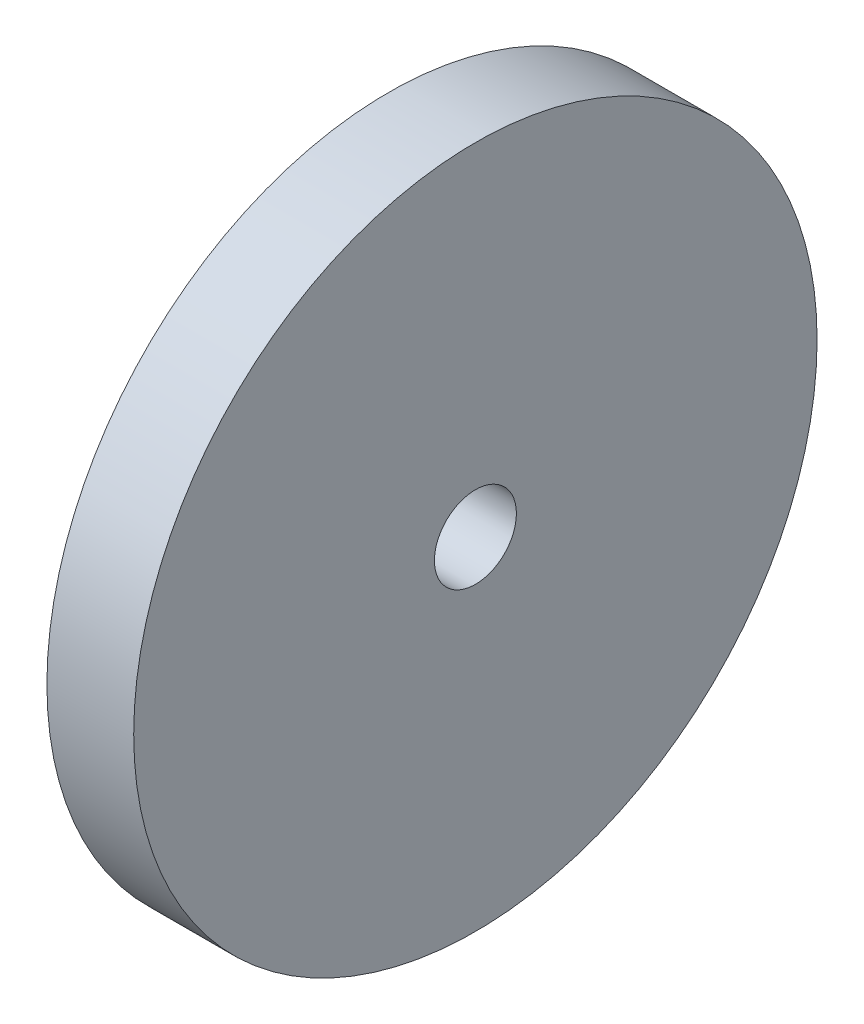
SolidWorks part; units mm, degrees
material "Maple"
ref_plane "Front Plane" through (0, 0, 0) normal (0, 0, 1) x (1, 0, 0)
ref_plane "Top Plane" through (0, 0, 0) normal (0, 1, 0) x (1, 0, 0)
ref_plane "Right Plane" through (0, 0, 0) normal (1, 0, 0) x (0, 0, -1)
sketch "Sketch1" plane through (0, 0, 0) normal (1, 0, 0) x (0, 0, -1)
  circle A0 centre (0, 0) radius 50
  circle A1 centre (0, 0) radius 6
  dimension "D1" = 100
  dimension "D2" = 12
extrude "Boss-Extrude1" add sketch "Sketch1" along normal blind 12.7
